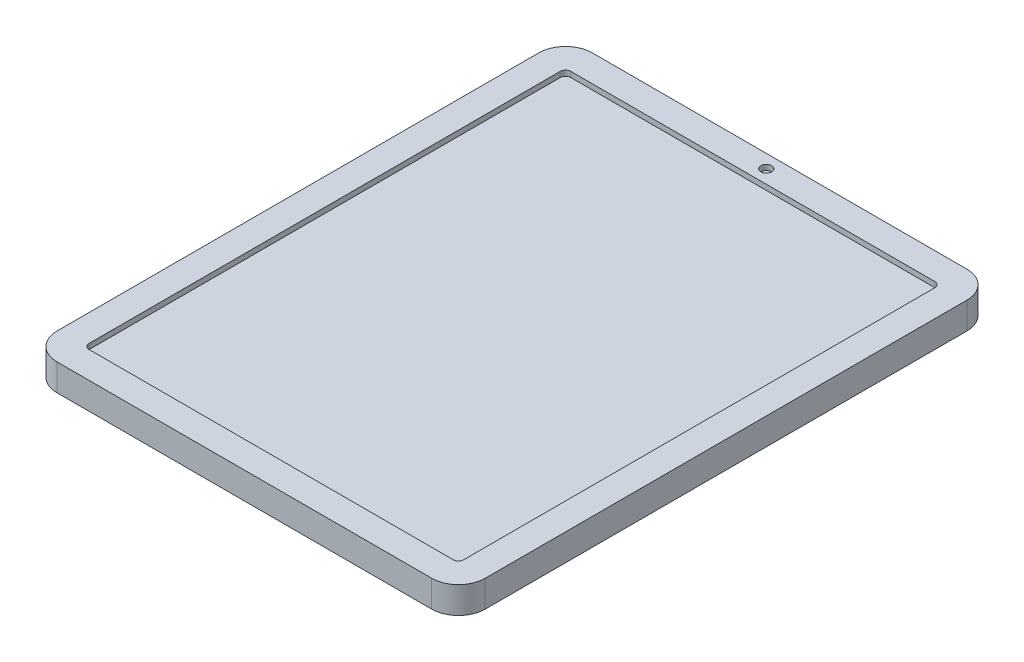
SolidWorks part; units mm, degrees
ref_plane "前视基准面" through (0, 0, 0) normal (0, 0, 1) x (1, 0, 0)
ref_plane "上视基准面" through (0, 0, 0) normal (0, 1, 0) x (1, 0, 0)
ref_plane "右视基准面" through (0, 0, 0) normal (1, 0, 0) x (0, 0, -1)
sketch "草图1" plane through (0, 0, 0) normal (0, 1, 0) x (1, 0, 0)
  line L1 (-80, -100) -> (80, -100)
  line L2 (-80, -100) -> (-80, 100)
  line L3 (-80, 100) -> (80, 100)
  line L4 (80, -100) -> (80, 100)
extrude "凸台-拉伸1" add sketch "草图1" along normal blind 10
sketch "草图2" plane through (0, 10, 0) normal (0, 1, 0) x (1, 0, 0)
  line L1 (-70, -90) -> (70, -90)
  line L2 (-70, -90) -> (-70, 90)
  line L3 (-70, 90) -> (70, 90)
  line L4 (70, -90) -> (70, 90)
  circle A0 centre (0, 95) radius 2
extrude "切除-拉伸1" cut sketch "草图2" against normal blind 2
fillet "圆角1" radius 10 4 edges at (-80, 5, -100) (80, 5, -100) (80, 5, 100) (-80, 5, 100)
fillet "圆角2" radius 2 4 edges at (70, 9, -90) (-70, 9, -90) (70, 9, 90) (-70, 9, 90)
